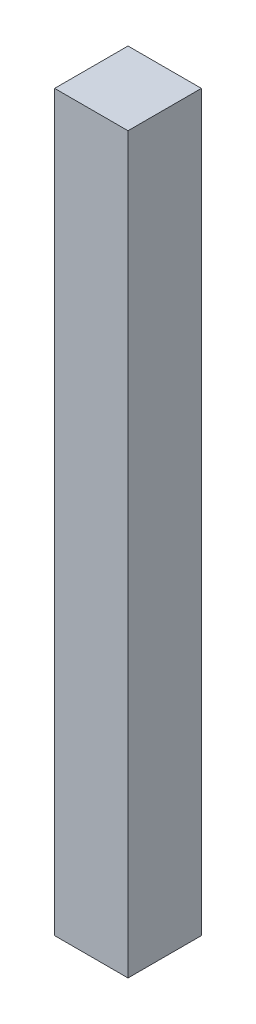
SolidWorks part; units mm, degrees
ref_plane "Ebene vorne" through (0, 0, 0) normal (0, 0, 1) x (1, 0, 0)
ref_plane "Ebene oben" through (0, 0, 0) normal (0, 1, 0) x (1, 0, 0)
ref_plane "Ebene rechts" through (0, 0, 0) normal (1, 0, 0) x (0, 0, -1)
sketch "Skizze2" plane through (0, 0, 0) normal (0, 1, 0) x (1, 0, 0)
  line L1 (-10, -10) -> (10, -10)
  line L2 (-10, -10) -> (-10, 10)
  line L3 (-10, 10) -> (10, 10)
  line L4 (10, -10) -> (10, 10)
  line L5 (-10, -10) -> (10, 10) construction
  line L6 (-10, 10) -> (10, -10) construction
  point P0 (0, 0)
  dimension "D1" = 20
  dimension "D2" = 20
extrude "Aufsatz-Linear austragen1" add sketch "Skizze2" along normal blind 200
